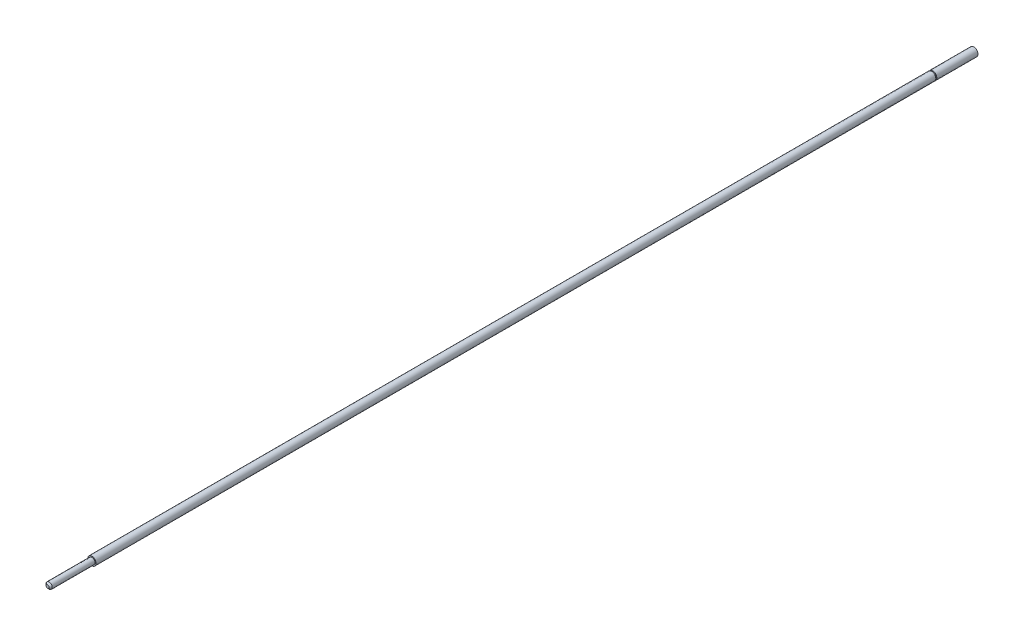
SolidWorks part; units mm, degrees
ref_plane "前视基准面" through (0, 0, 0) normal (0, 0, 1) x (1, 0, 0)
ref_plane "上视基准面" through (0, 0, 0) normal (0, 1, 0) x (1, 0, 0)
ref_plane "右视基准面" through (0, 0, 0) normal (1, 0, 0) x (0, 0, -1)
sketch "草图1" plane through (0, 0, 0) normal (0, 0, 1) x (1, 0, 0)
  circle A0 centre (0, 0) radius 4
  dimension "D1" = 8
extrude "凸台-拉伸1" add sketch "草图1" along normal blind 39.5
sketch "草图2" plane through (0, 0, 39.5) normal (0, 0, 1) x (1, 0, 0)
  circle A0 centre (0, 0) radius 3
  dimension "D1" = 6
extrude "凸台-拉伸2" add sketch "草图2" along normal blind 1
sketch "草图3" plane through (0, 0, 40.5) normal (0, 0, 1) x (1, 0, 0)
  circle A0 centre (0, 0) radius 4
  dimension "D1" = 8
extrude "凸台-拉伸3" add sketch "草图3" along normal blind 805.5
sketch "草图4" plane through (0, 0, 846) normal (0, 0, 1) x (1, 0, 0)
  circle A0 centre (0, 0) radius 3
  dimension "D1" = 6
extrude "凸台-拉伸4" add sketch "草图4" along normal blind 42.5
sketch "草图7" plane through (0, 0, 0) normal (0, 0, -1) x (-1, 0, 0)
  line L0 (3, 0) -> (1.5, -2.5981)
  line L1 (1.5, -2.5981) -> (-1.5, -2.5981)
  line L2 (-1.5, -2.5981) -> (-3, 0)
  line L3 (-3, 0) -> (-1.5, 2.5981)
  line L4 (-1.5, 2.5981) -> (1.5, 2.5981)
  line L5 (1.5, 2.5981) -> (3, 0)
  circle A0 centre (0, 0) radius 3 construction
  dimension "D1" = 6
extrude "切除-拉伸1" cut sketch "草图7" against normal blind 5
chamfer "倒角1" distance 1.5 angle 45 1 edges at (3, 0, 888.5)
